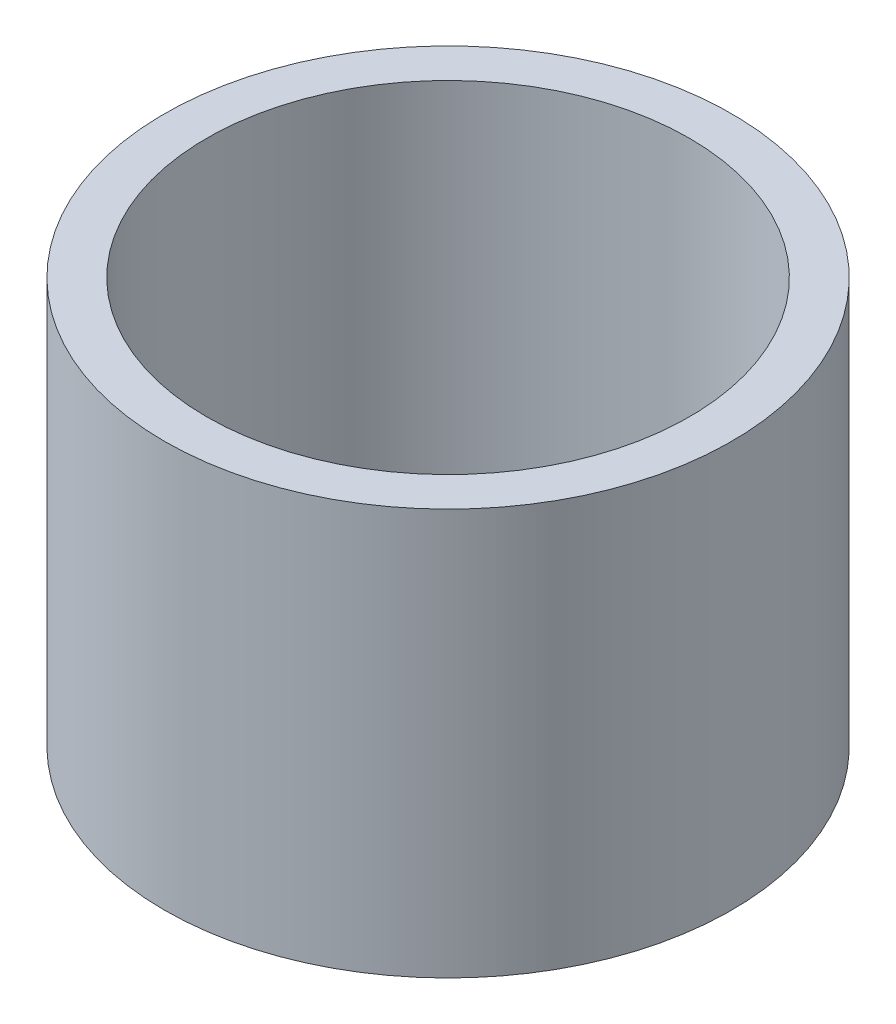
SolidWorks part; units mm, degrees
ref_plane "Alzado" through (0, 0, 0) normal (0, 0, 1) x (1, 0, 0)
ref_plane "Planta" through (0, 0, 0) normal (0, 1, 0) x (1, 0, 0)
ref_plane "Vista lateral" through (0, 0, 0) normal (1, 0, 0) x (0, 0, -1)
sketch "Croquis3" plane through (0, 0, 0) normal (0, 1, 0) x (1, 0, 0)
  circle A0 centre (0, 0) radius 29.72
  circle A1 centre (0, 0) radius 34.93
  dimension "D1" = 59.44
  dimension "D2" = 69.86
extrude "Saliente-Extruir2" add sketch "Croquis3" along normal blind 50
